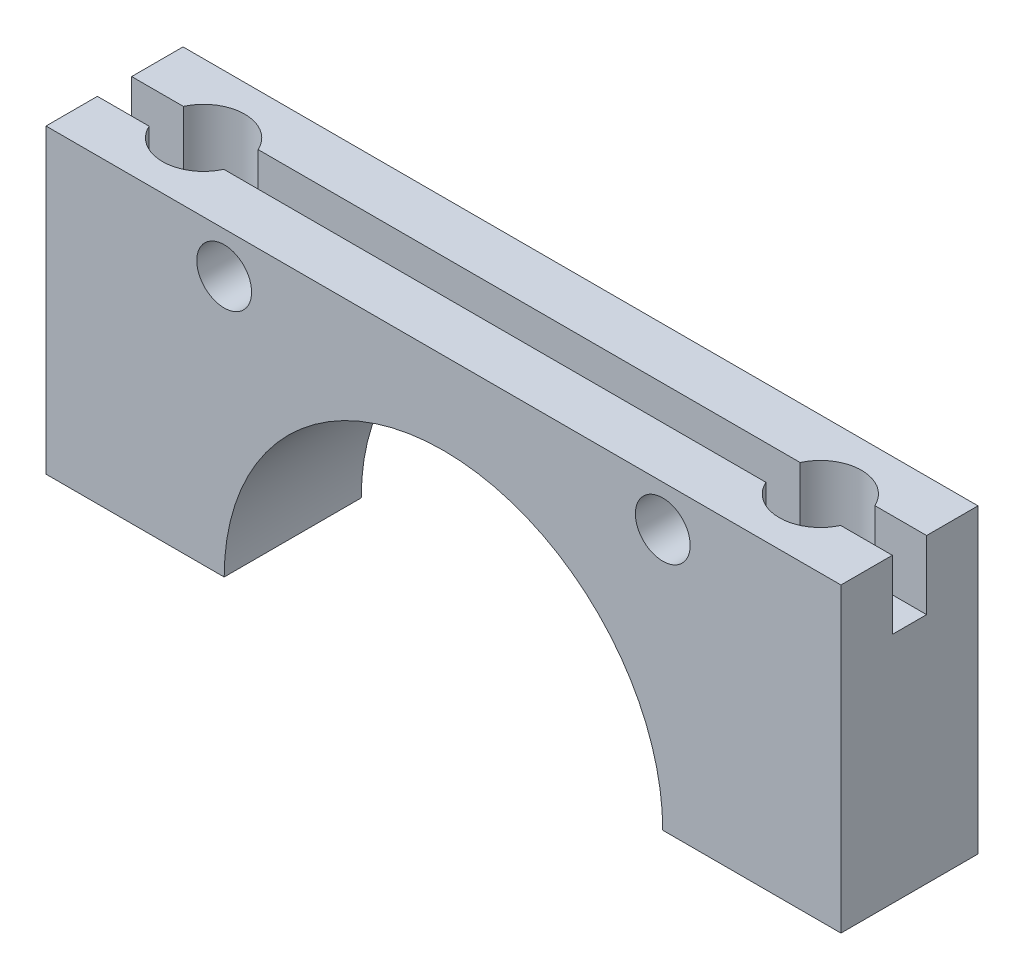
SolidWorks part; units mm, degrees
ref_plane "前视基准面" through (0, 0, 0) normal (0, 0, 1) x (1, 0, 0)
ref_plane "上视基准面" through (0, 0, 0) normal (0, 1, 0) x (1, 0, 0)
ref_plane "右视基准面" through (0, 0, 0) normal (1, 0, 0) x (0, 0, -1)
sketch "草图1" plane through (0, 0, 0) normal (0, 0, 1) x (1, 0, 0)
  line L0 (-69.3343, 6.5745) -> (-69.3343, 28.5745)
  line L2 (-69.3343, 8.5745) -> (-11.3343, 8.5745) construction
  line L3 (-69.3343, 8.5745) -> (-69.3343, 4.5745) construction
  line L4 (-69.3343, 4.5745) -> (-11.3343, 4.5745) construction
  line L5 (-11.3343, 8.5745) -> (-11.3343, 4.5745) construction
  line L8 (-69.3343, 6.5745) -> (-56.3343, 6.5745)
  line L10 (-11.3343, 6.5745) -> (-24.3343, 6.5745)
  line L11 (-69.3343, 28.5745) -> (-11.3343, 28.5745)
  line L12 (-11.3343, 28.5745) -> (-11.3343, 6.5745)
  circle A0 centre (-40.3343, 6.5745) radius 16 construction
  circle A1 centre (-40.3343, 6.5745) radius 19 construction
  arc A3 (-56.3343, 6.5745) -> (-24.3343, 6.5745) centre (-40.3343, 6.5745) cw
  point P9 (-69.3343, 6.5745)
  point P11 (-40.3343, 8.5745)
  dimension "D1" = 4
  dimension "D2" = 29
  dimension "D3" = 22
extrude "凸台-拉伸1" add sketch "草图1" along normal blind 10
sketch "草图2" plane through (0, 6.5745, 0) normal (0, -1, 0) x (1, 0, 0)
  line L0 (-69.3343, 10) -> (-56.3343, 10) construction
  line L1 (-69.3343, 10) -> (-69.3343, 0) construction
  line L2 (-24.3343, 10) -> (-11.3343, 10) construction
  line L3 (-11.3343, 10) -> (-11.3343, 0) construction
  circle A0 centre (-62.8343, 5) radius 1.6
  circle A1 centre (-17.8343, 5) radius 1.6
  point P0 (-62.8343, 10)
  point P1 (-69.3343, 5)
  point P4 (-17.8343, 10)
  point P7 (-11.3343, 5)
  point P10 (-62.8343, 5)
  point P13 (-17.8343, 5)
extrude "切除-拉伸1" cut sketch "草图2" against normal blind 27
sketch "草图3" plane through (0, 28.5745, 0) normal (0, 1, 0) x (1, 0, 0)
  circle A0 centre (-62.8343, -5) radius 3
  circle A1 centre (-17.8343, -5) radius 3
extrude "切除-拉伸2" cut sketch "草图3" against normal blind 15
sketch "草图4" plane through (0, 28.5745, 0) normal (0, 1, 0) x (1, 0, 0)
  line L0 (-69.3343, -10) -> (-69.3343, 0) construction
  line L1 (-69.3343, -3.75) -> (-11.3343, -3.75)
  line L2 (-69.3343, -3.75) -> (-69.3343, -6.25)
  line L3 (-69.3343, -6.25) -> (-11.3343, -6.25)
  line L4 (-11.3343, -3.75) -> (-11.3343, -6.25)
  line L5 (-11.3343, 0) -> (-69.3343, 0) construction
  point P4 (-69.3343, -5)
  point P5 (-69.3343, -5)
  point P6 (-40.3343, -3.75)
  point P9 (-40.3343, 0)
  dimension "D1" = 2.5
extrude "切除-拉伸4" cut sketch "草图4" against normal blind 5
sketch "草图5" plane through (0, 0, 10) normal (0, 0, 1) x (1, 0, 0)
  line L0 (-11.3343, 28.5745) -> (-69.3343, 28.5745) construction
  circle A0 centre (-56.3343, 25.5745) radius 2
  circle A1 centre (-24.3343, 25.5745) radius 2
  dimension "D1" = 3
  dimension "D2" = 3
extrude "切除-拉伸5" cut sketch "草图5" against normal blind 5
